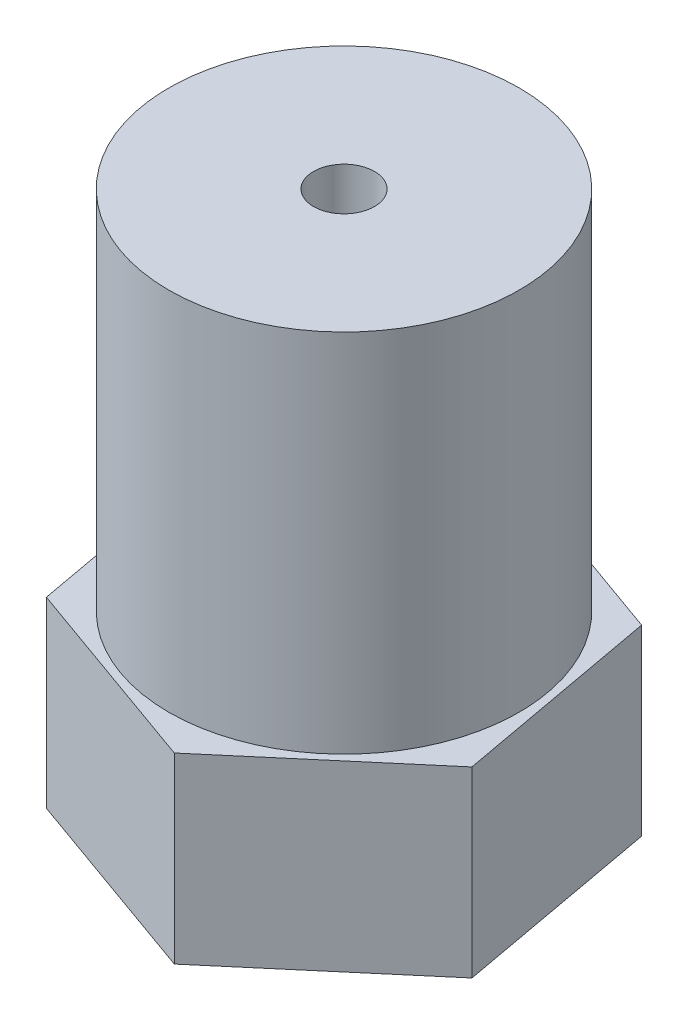
SolidWorks part; units mm, degrees
ref_plane "前视基准面" through (0, 0, 0) normal (0, 0, 1) x (1, 0, 0)
ref_plane "上视基准面" through (0, 0, 0) normal (0, 1, 0) x (1, 0, 0)
ref_plane "右视基准面" through (0, 0, 0) normal (1, 0, 0) x (0, 0, -1)
sketch "草图1" plane through (0, 0, 0) normal (0, 1, 0) x (1, 0, 0)
  line L1 (5.2802, 4.4882) -> (-1.2468, 6.8169)
  line L2 (-1.2468, 6.8169) -> (-6.527, 2.3287)
  line L3 (-6.527, 2.3287) -> (-5.2802, -4.4882)
  line L4 (-5.2802, -4.4882) -> (1.2468, -6.8169)
  line L5 (1.2468, -6.8169) -> (6.527, -2.3287)
  line L6 (6.527, -2.3287) -> (5.2802, 4.4882)
  circle A0 centre (0, 0) radius 6.0016 construction
extrude "凸台-拉伸1" add sketch "草图1" along normal blind 6
sketch "草图2" plane through (0, 6, 0) normal (0, 1, 0) x (1, 0, 0)
  circle A0 centre (0, 0) radius 2
extrude "切除-拉伸1" cut sketch "草图2" against normal blind 6
sketch "草图3" plane through (0, 6, 0) normal (0, 1, 0) x (1, 0, 0)
  circle A0 centre (0, 0) radius 5.75
extrude "凸台-拉伸2" add sketch "草图3" along normal blind 12
sketch "草图4" plane through (0, 18, 0) normal (0, 1, 0) x (1, 0, 0)
  circle A0 centre (0, 0) radius 1
extrude "切除-拉伸2" cut sketch "草图4" against normal blind 12
